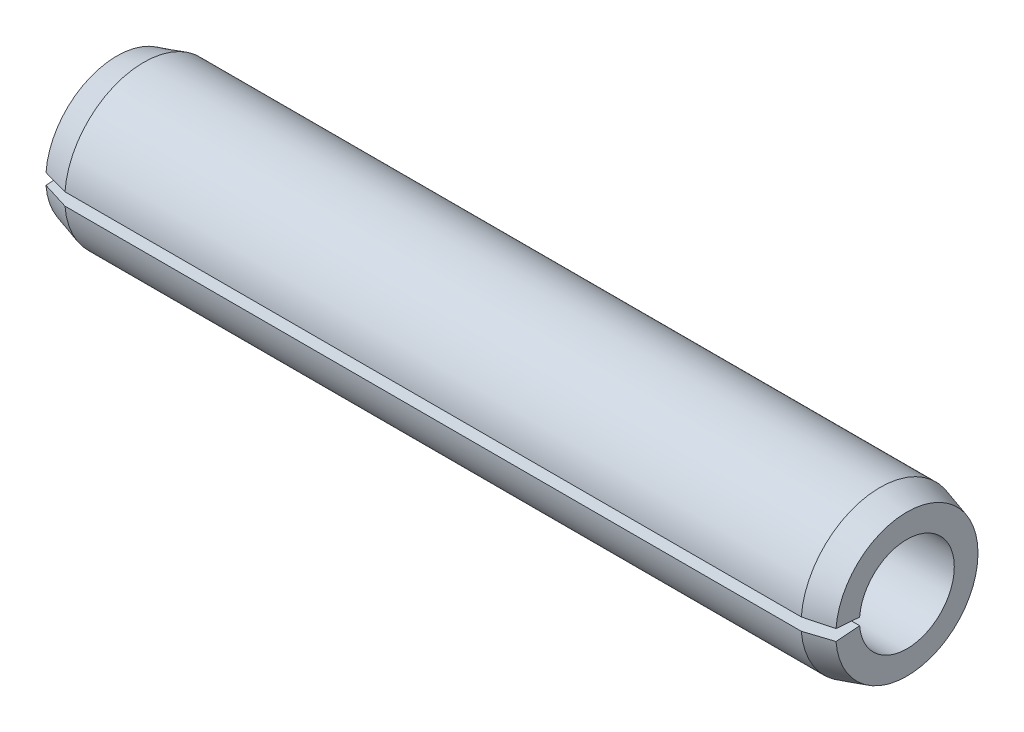
SolidWorks part; units mm, degrees
ref_plane "Plane1" through (0, 0, 0) normal (0, 0, 1) x (1, 0, 0)
ref_plane "Plane2" through (0, 0, 0) normal (0, 1, 0) x (1, 0, 0)
ref_plane "Plane3" through (0, 0, 0) normal (1, 0, 0) x (0, 0, -1)
sketch "BodySke" plane through (0, 0, 0) normal (0, 0, 1) x (1, 0, 0)
  line L0 (-9.525, 0) -> (111.125, 0) construction
  line L1 (0, 6) -> (100, 6)
  line L2 (100, 6) -> (100, 9)
  line L3 (100, 9) -> (96.6, 10)
  line L4 (96.6, 10) -> (3.4, 10)
  line L5 (3.4, 10) -> (0, 9)
  line L7 (0, 9) -> (0, 6)
  dimension "Diameter" = 20
  dimension "Thickness" = 4
  dimension "Length" = 100
  dimension "Chamfer_len" = 3.4
  dimension "D1" = 18
  dimension "D2" = 18
  dimension "D3" = 3.4
revolve "Body" add sketch "BodySke" angle 360 about L0
sketch "GapSke" plane through (0, 0, 0) normal (-1, 0, 0) x (0, -1, 0)
  line L0 (0, 0) -> (0.8003, 10.1686)
  line L1 (0, -3.175) -> (0, 12.7) construction
  line L2 (0, 0) -> (-0.8003, 10.1686)
  arc A0 (0.8003, 10.1686) -> (-0.8003, 10.1686) centre (0, 0) ccw
  dimension "Gap_ang" = 9
  dimension "D1" = 10.2
extrude "Gap" cut sketch "GapSke" against normal through all
equation "\"D1@GapSke\" = \"Diameter@BodySke\" * 0.51"
equation "\"D1@BodySke\" = \"Diameter@BodySke\" -  ( \"Thickness@BodySke\" / 2 ) "
equation "\"D2@BodySke\" = \"D1@BodySke\""
equation "\"D3@BodySke\" = \"Chamfer_len@BodySke\""
